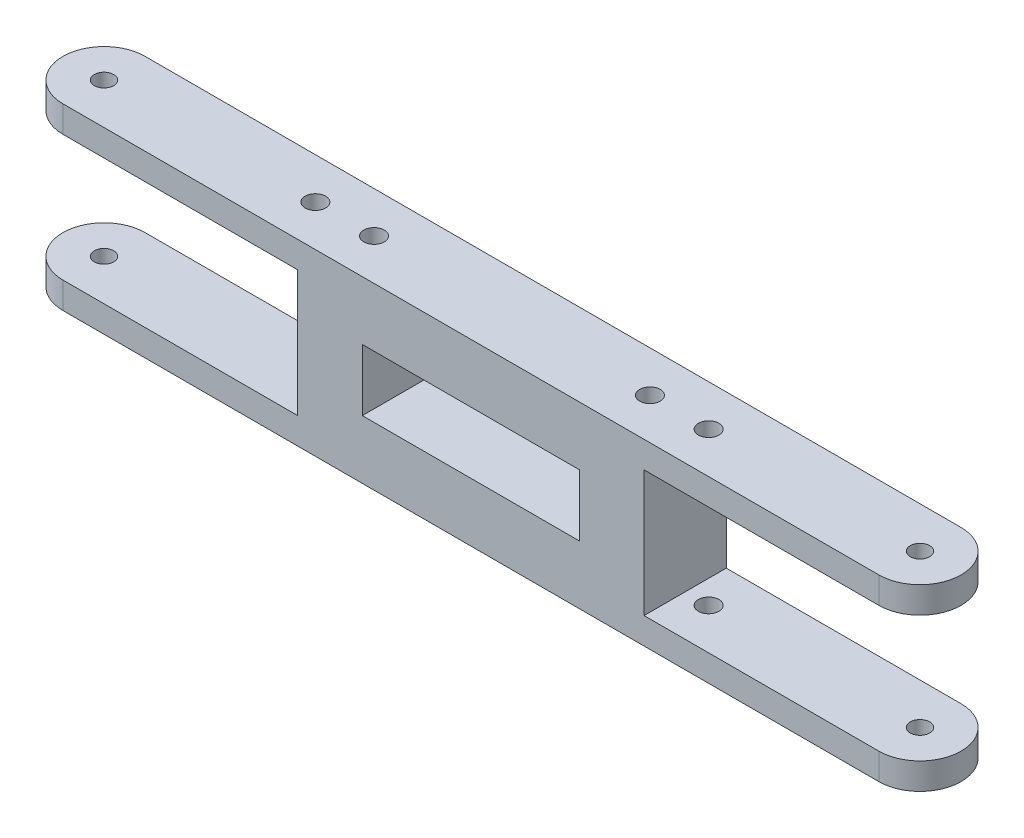
SolidWorks part; units mm, degrees
ref_plane "正面" through (0, 0, 0) normal (0, 0, 1) x (1, 0, 0)
ref_plane "平面" through (0, 0, 0) normal (0, 1, 0) x (1, 0, 0)
ref_plane "右側面" through (0, 0, 0) normal (1, 0, 0) x (0, 0, -1)
sketch "ｽｹｯﾁ1" plane through (0, 0, 0) normal (0, 1, 0) x (1, 0, 0)
  line L0 (0, 7) -> (51, 7)
  line L1 (51, 7) -> (51, -7)
  line L2 (51, -7) -> (0, -7)
  line L3 (-16.775, 0) -> (16.775, 0) construction
  arc A0 (0, 7) -> (0, -7) centre (0, 0) ccw
  circle A1 centre (0, 0) radius 1.65
  circle A2 centre (46, 0) radius 1.75
  circle A3 centre (36, 0) radius 1.75
  dimension "D2" = 7
  dimension "D3" = 3.3
  dimension "D4" = 3.5
  dimension "D5" = 3.5
  dimension "D6" = 5
  dimension "D7" = 10
  dimension "D1" = 51
extrude "ﾎﾞｽ - 押し出し1" add sketch "ｽｹｯﾁ1" along normal blind 30.5
sketch "ｽｹｯﾁ2" plane through (0, 0, 7) normal (0, 0, 1) x (1, 0, 0)
  line L0 (0, 26) -> (-7, 26)
  line L1 (0, -7.7) -> (0, 7.7) construction
  line L2 (-7, 30.5) -> (-7, 0) construction
  line L3 (-7, 26) -> (-7, 4.5)
  line L4 (-7, 4.5) -> (0, 4.5)
  line L6 (7.7, 0) -> (-7.7, 0) construction
  line L7 (0, 26) -> (40, 26)
  line L8 (40, 26) -> (40, 4.5)
  line L9 (40, 4.5) -> (0, 4.5)
  dimension "D1" = 21.5
  dimension "D2" = 4.5
  dimension "D3" = 40
extrude "ｶｯﾄ - 押し出し1" cut sketch "ｽｹｯﾁ2" against normal through all
sketch "ｽｹｯﾁ3" plane through (0, 0, 7) normal (0, 0, 1) x (1, 0, 0)
  line L0 (51, 10) -> (31, 10)
  line L1 (51, 30.5) -> (51, 0) construction
  line L2 (31, 10) -> (31, 20.5)
  line L3 (31, 20.5) -> (51, 20.5)
  line L4 (51, 20.5) -> (51, 10)
  line L5 (0, 30.5) -> (51, 30.5) construction
  dimension "D1" = 10
  dimension "D2" = 10.5
  dimension "D3" = 20
extrude "ｶｯﾄ - 押し出し2" cut sketch "ｽｹｯﾁ3" against normal through all
sketch "ｽｹｯﾁ4" plane through (0, 0, 7) normal (0, 0, 1) x (1, 0, 0)
  line L0 (51, 30.5) -> (69.5, 30.5)
  line L1 (69.5, 30.5) -> (69.5, 20.5)
  line L2 (69.5, 20.5) -> (51, 20.5)
  line L3 (51, 20.5) -> (51, 30.5)
  line L4 (51, 10) -> (69.5, 10)
  line L5 (69.5, 10) -> (69.5, 0)
  line L6 (69.5, 0) -> (51, 0)
  line L7 (7.7, 0) -> (-7.7, 0) construction
  line L8 (51, 10) -> (51, 0) construction
  line L9 (51, 0) -> (51, 10)
  dimension "D1" = 18.5
  dimension "D2" = 18.5
extrude "ﾎﾞｽ - 押し出し2" add sketch "ｽｹｯﾁ4" against normal blind 14
mirror "ﾐﾗｰ1" about plane through (69.5, 10, -7) normal (1, 0, 0) of bodies 111 108
mirror "ﾐﾗｰ2" about plane through (69.5, 30.5, -7) normal (1, 0, 0) of bodies 110 107
sketch "ｽｹｯﾁ5" plane through (0, 0, -7) normal (0, 0, -1) x (-1, 0, 0)
  line L0 (-99, 20.5) -> (-88, 20.5)
  line L1 (-88, 20.5) -> (-88, 10)
  line L2 (-40, 10) -> (-99, 10) construction
  line L3 (-88, 10) -> (-99, 10)
  line L4 (-99, 10) -> (-99, 20.5)
  line L5 (-51, 20.5) -> (-40, 20.5)
  line L6 (-40, 20.5) -> (-40, 10)
  line L7 (-40, 10) -> (-51, 10)
  line L8 (-51, 10) -> (-51, 20.5)
extrude "ﾎﾞｽ - 押し出し3" add sketch "ｽｹｯﾁ5" against normal blind 14
equation "\"D1@ｽｹｯﾁ3\"=15.25-5.25mm"
